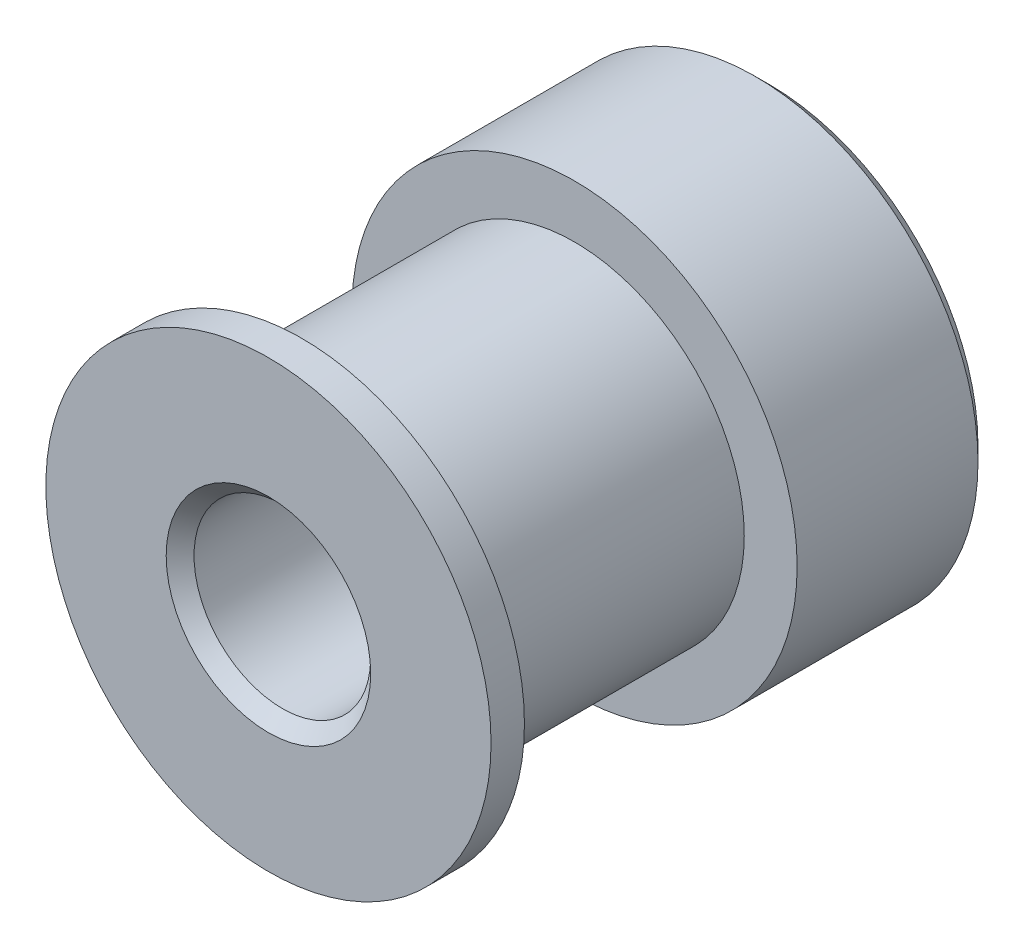
SolidWorks part; units mm, degrees
ref_plane "Alzado" through (0, 0, 0) normal (0, 0, 1) x (1, 0, 0)
ref_plane "Planta" through (0, 0, 0) normal (0, 1, 0) x (1, 0, 0)
ref_plane "Vista lateral" through (0, 0, 0) normal (1, 0, 0) x (0, 0, -1)
sketch "Croquis1" plane through (0, 0, 0) normal (0, 0, 1) x (1, 0, 0)
  circle A0 centre (0, 0) radius 8
  dimension "D1" = 16
extrude "Saliente-Extruir1" add sketch "Croquis1" along normal blind 7
sketch "Croquis2" plane through (0, 0, 7) normal (0, 0, 1) x (1, 0, 0)
  circle A0 centre (0, 0) radius 6.1
  dimension "D1" = 12.2
extrude "Saliente-Extruir2" add sketch "Croquis2" along normal blind 9.8
sketch "Croquis3" plane through (0, 0, 16.8) normal (0, 0, 1) x (1, 0, 0)
  circle A0 centre (0, 0) radius 8
  dimension "D1" = 16
extrude "Saliente-Extruir3" add sketch "Croquis3" along normal blind 1.2
sketch "Croquis4" plane through (0, 0, 18) normal (0, 0, 1) x (1, 0, 0)
  circle A0 centre (0, 0) radius 3.175
  dimension "D1" = 6.35
extrude "Cortar-Extruir1" cut sketch "Croquis4" against normal through all
chamfer "Chaflán1" distance 0.5 angle 45 3 edges at (8, 0, 0) (3.175, 0, 0) (3.175, 0, 18)
sketch "Croquis5" plane through (0, 0, 0) normal (1, 0, 0) x (0, 0, -1)
  line L0 (0, 0) -> (-3.5, 0) construction
  circle A0 centre (-3.5, 0) radius 1.5
  dimension "D2" = 3
  dimension "D1" = 3.5
extrude "Cortar-Extruir2" cut sketch "Croquis5" against normal through all
sketch "Croquis6" plane through (0, 0, 0) normal (0, 1, 0) x (1, 0, 0)
  line L0 (0, 0) -> (0, -3.5) construction
  circle A0 centre (0, -3.5) radius 1.5
  dimension "D2" = 3
  dimension "D1" = 3.5
extrude "Cortar-Extruir3" cut sketch "Croquis6" against normal through all
